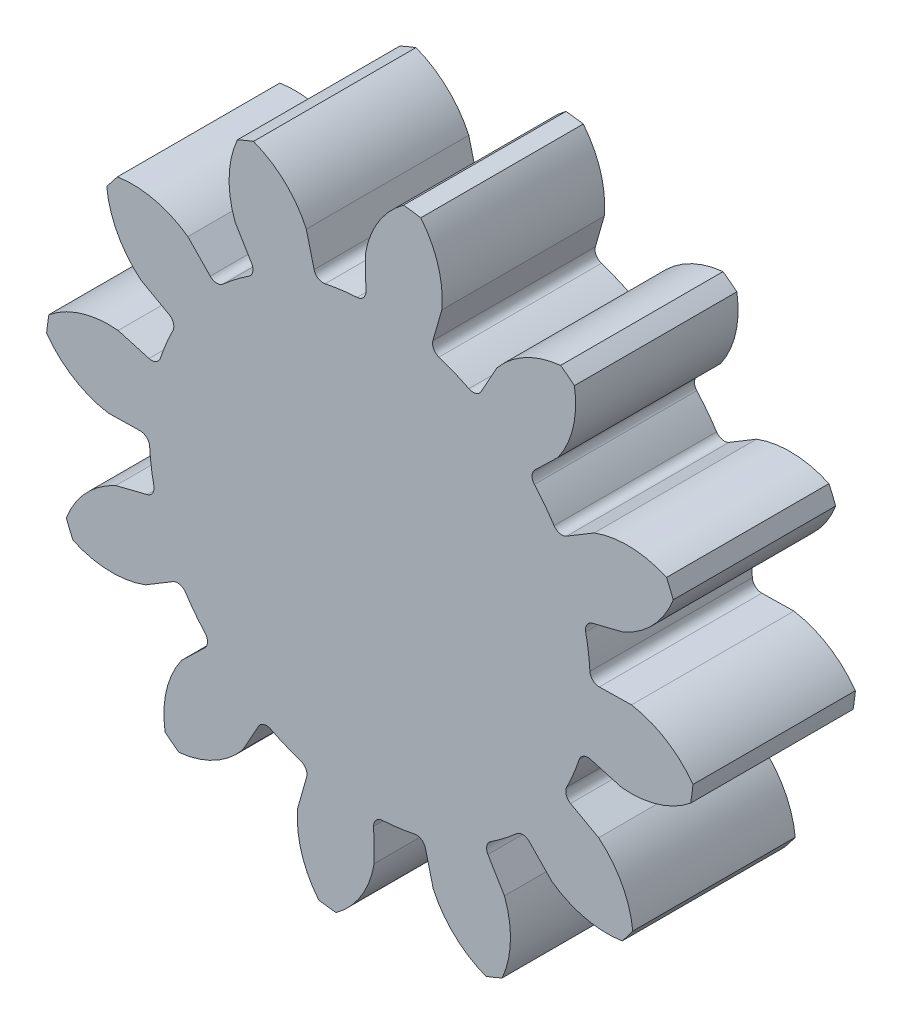
SolidWorks part; units mm, degrees
material "AISI 1045 钢，冷拔"
ref_plane "Front" through (0, 0, 0) normal (0, 0, 1) x (1, 0, 0)
ref_plane "Top" through (0, 0, 0) normal (0, 1, 0) x (1, 0, 0)
ref_plane "Right" through (0, 0, 0) normal (1, 0, 0) x (0, 0, -1)
sketch "草图1" plane through (0, 0, 0) normal (0, 0, 1) x (1, 0, 0)
  line L0 (0, 0) -> (-22.86, 0) construction
  line L1 (-22.86, 0) -> (-22.86, 5) construction
  line L2 (-22.86, 0) -> (-21.3149, 4.7553) construction
  line L3 (-22.86, 0) -> (-19.9211, 4.0451) construction
  line L4 (-22.86, 0) -> (-18.8149, 2.9389) construction
  line L5 (-22.86, 0) -> (-18.1047, 1.5451) construction
  line L6 (-22.86, 0) -> (-17.86, 0) construction
  line L7 (-22.86, 0) -> (-18.1047, -1.5451) construction
  line L8 (-22.86, 0) -> (-18.8149, -2.9389) construction
  line L9 (-22.86, 0) -> (-19.9211, -4.0451) construction
  line L10 (-22.86, 0) -> (-21.3149, -4.7553) construction
  line L11 (-22.86, 0) -> (-22.86, -5) construction
  line L12 (-22.86, 0) -> (-24.4051, -4.7553) construction
  line L21 (0, 0) -> (0, 8.5725) construction
  line L22 (-0.1365, 8.0544) -> (-0.1197, 7.0655)
  line L23 (0, 0) -> (1.3006, 9.8793) construction
  line L24 (0, 0) -> (-1.3054, 9.9157) construction
  line L25 (2.2165, 7.7446) -> (1.9443, 6.7938)
  line L26 (3.909, 7.0435) -> (3.4291, 6.1788)
  line L27 (5.7918, 5.5988) -> (5.0807, 4.9114)
  line L28 (6.907, 4.1454) -> (6.0591, 3.6365)
  line L29 (7.8152, 1.9528) -> (6.8558, 1.713)
  line L30 (8.0544, 0.1365) -> (7.0655, 0.1197)
  line L31 (7.7446, -2.2165) -> (6.7938, -1.9443)
  line L32 (7.0435, -3.909) -> (6.1788, -3.4291)
  line L33 (5.5988, -5.7918) -> (4.9114, -5.0807)
  line L34 (4.1454, -6.907) -> (3.6365, -6.0591)
  line L35 (1.9528, -7.8152) -> (1.713, -6.8558)
  line L36 (0.1365, -8.0544) -> (0.1197, -7.0655)
  line L37 (-2.2165, -7.7446) -> (-1.9443, -6.7938)
  line L38 (-3.909, -7.0435) -> (-3.4291, -6.1788)
  line L39 (-5.7918, -5.5988) -> (-5.0807, -4.9114)
  line L40 (-6.907, -4.1454) -> (-6.0591, -3.6365)
  line L41 (-7.8152, -1.9528) -> (-6.8558, -1.713)
  line L42 (-8.0544, -0.1365) -> (-7.0655, -0.1197)
  line L43 (-7.7446, 2.2165) -> (-6.7938, 1.9443)
  line L44 (-7.0435, 3.909) -> (-6.1788, 3.4291)
  line L45 (-5.5988, 5.7918) -> (-4.9114, 5.0807)
  line L46 (-4.1454, 6.907) -> (-3.6365, 6.0591)
  line L47 (-1.9528, 7.8152) -> (-1.713, 6.8558)
  line L56 (-22.86, 0) -> (-25.7989, -4.0451) construction
  line L57 (-22.86, 0) -> (-26.9051, -2.9389) construction
  line L58 (-22.86, 0) -> (-27.6153, -1.5451) construction
  line L59 (-22.86, 0) -> (-27.86, 0) construction
  line L60 (-22.86, 0) -> (-27.6153, 1.5451) construction
  line L61 (-22.86, 0) -> (-26.9051, 2.9389) construction
  line L62 (-22.86, 0) -> (-25.7989, 4.0451) construction
  line L63 (-22.86, 0) -> (-24.4051, 4.7553) construction
  circle A0 centre (0, 0) radius 6.7866 construction
  circle A1 centre (0, 0) radius 8.0555 construction
  circle A2 centre (0, 0) radius 8.5725 construction
  circle A3 centre (0, 0) radius 10.0012 construction
  arc A4 (0, 8.5725) -> (2.7551, 7.5697) centre (0, 4.2862) cw construction
  arc A5 (0, 8.5725) -> (-0.1365, 8.0544) centre (2.7551, 7.5697) ccw
  arc A6 (0, 8.5725) -> (1.0392, 9.9471) centre (2.7551, 7.5697) cw
  arc A7 (-0.3891, 6.7754) -> (-0.8858, 6.7285) centre (0, 0) ccw
  arc A8 (-0.3891, 6.7754) -> (-0.1197, 7.0655) centre (-0.4054, 7.0607) ccw
  arc A9 (1.0392, 9.9471) -> (1.5707, 9.8771) centre (0, 0) cw
  arc A10 (2.2187, 8.2804) -> (1.5707, 9.8771) centre (-0.7021, 8.0249) ccw
  arc A11 (2.2187, 8.2804) -> (2.2165, 7.7446) centre (-0.7021, 8.0249) cw
  arc A12 (2.1294, 6.4438) -> (1.9443, 6.7938) centre (2.2191, 6.7152) cw
  arc A13 (2.1294, 6.4438) -> (2.5971, 6.27) centre (0, 0) cw
  arc A14 (3.0508, 6.0622) -> (2.5971, 6.27) centre (0, 0) ccw
  arc A15 (3.0508, 6.0622) -> (3.4291, 6.1788) centre (3.1792, 6.3174) ccw
  arc A16 (4.2862, 7.424) -> (3.909, 7.0435) centre (6.1709, 5.178) ccw
  arc A17 (4.2862, 7.424) -> (5.8736, 8.0948) centre (6.1709, 5.178) cw
  arc A18 (5.8736, 8.0948) -> (6.2988, 7.7685) centre (0, 0) cw
  arc A19 (6.0617, 6.0617) -> (6.2988, 7.7685) centre (3.4044, 7.3008) ccw
  arc A20 (6.0617, 6.0617) -> (5.7918, 5.5988) centre (3.4044, 7.3008) cw
  arc A21 (5.066, 4.5158) -> (5.0807, 4.9114) centre (5.2793, 4.706) cw
  arc A22 (5.066, 4.5158) -> (5.3841, 4.1314) centre (0, 0) cw
  arc A23 (5.6731, 3.7246) -> (5.3841, 4.1314) centre (0, 0) ccw
  arc A24 (5.6731, 3.7246) -> (6.0591, 3.6365) centre (5.912, 3.8815) ccw
  arc A25 (7.424, 4.2863) -> (6.907, 4.1454) centre (7.9331, 1.3988) ccw
  arc A26 (7.424, 4.2863) -> (9.1341, 4.0736) centre (7.9331, 1.3988) cw
  arc A27 (9.1341, 4.0736) -> (9.3392, 3.5783) centre (0, 0) cw
  arc A28 (8.2804, 2.2187) -> (9.3392, 3.5783) centre (6.5987, 4.6205) ccw
  arc A29 (8.2804, 2.2187) -> (7.8152, 1.9528) centre (6.5987, 4.6205) cw
  arc A30 (6.6452, 1.3778) -> (6.8558, 1.713) centre (6.925, 1.4358) cw
  arc A31 (6.6452, 1.3778) -> (6.7285, 0.8858) centre (0, 0) cw
  arc A32 (6.7754, 0.3891) -> (6.7285, 0.8858) centre (0, 0) ccw
  arc A33 (6.7754, 0.3891) -> (7.0655, 0.1197) centre (7.0607, 0.4054) ccw
  arc A34 (8.5725, 0) -> (8.0544, 0.1365) centre (7.5697, -2.7551) ccw
  arc A35 (8.5725, 0) -> (9.9471, -1.0392) centre (7.5697, -2.7551) cw
  arc A36 (9.9471, -1.0392) -> (9.8771, -1.5707) centre (0, 0) cw
  arc A37 (8.2804, -2.2187) -> (9.8771, -1.5707) centre (8.0249, 0.7021) ccw
  arc A38 (8.2804, -2.2187) -> (7.7446, -2.2165) centre (8.0249, 0.7021) cw
  arc A39 (6.4438, -2.1294) -> (6.7938, -1.9443) centre (6.7152, -2.2191) cw
  arc A40 (6.4438, -2.1294) -> (6.27, -2.5971) centre (0, 0) cw
  arc A41 (6.0622, -3.0508) -> (6.27, -2.5971) centre (0, 0) ccw
  arc A42 (6.0622, -3.0508) -> (6.1788, -3.4291) centre (6.3174, -3.1792) ccw
  arc A43 (7.424, -4.2862) -> (7.0435, -3.909) centre (5.178, -6.1709) ccw
  arc A44 (7.424, -4.2862) -> (8.0948, -5.8736) centre (5.178, -6.1709) cw
  arc A45 (8.0948, -5.8736) -> (7.7685, -6.2988) centre (0, 0) cw
  arc A46 (6.0617, -6.0617) -> (7.7685, -6.2988) centre (7.3008, -3.4044) ccw
  arc A47 (6.0617, -6.0617) -> (5.5988, -5.7918) centre (7.3008, -3.4044) cw
  arc A48 (4.5158, -5.066) -> (4.9114, -5.0807) centre (4.706, -5.2793) cw
  arc A49 (4.5158, -5.066) -> (4.1314, -5.3841) centre (0, 0) cw
  arc A50 (3.7246, -5.6731) -> (4.1314, -5.3841) centre (0, 0) ccw
  arc A51 (3.7246, -5.6731) -> (3.6365, -6.0591) centre (3.8815, -5.912) ccw
  arc A52 (4.2863, -7.424) -> (4.1454, -6.907) centre (1.3988, -7.9331) ccw
  arc A53 (4.2863, -7.424) -> (4.0736, -9.1341) centre (1.3988, -7.9331) cw
  arc A54 (4.0736, -9.1341) -> (3.5783, -9.3392) centre (0, 0) cw
  arc A55 (2.2187, -8.2804) -> (3.5783, -9.3392) centre (4.6205, -6.5987) ccw
  arc A56 (2.2187, -8.2804) -> (1.9528, -7.8152) centre (4.6205, -6.5987) cw
  arc A57 (1.3778, -6.6452) -> (1.713, -6.8558) centre (1.4358, -6.925) cw
  arc A58 (1.3778, -6.6452) -> (0.8858, -6.7285) centre (0, 0) cw
  arc A59 (0.3891, -6.7754) -> (0.8858, -6.7285) centre (0, 0) ccw
  arc A60 (0.3891, -6.7754) -> (0.1197, -7.0655) centre (0.4054, -7.0607) ccw
  arc A61 (0, -8.5725) -> (0.1365, -8.0544) centre (-2.7551, -7.5697) ccw
  arc A62 (0, -8.5725) -> (-1.0392, -9.9471) centre (-2.7551, -7.5697) cw
  arc A63 (-1.0392, -9.9471) -> (-1.5707, -9.8771) centre (0, 0) cw
  arc A64 (-2.2187, -8.2804) -> (-1.5707, -9.8771) centre (0.7021, -8.0249) ccw
  arc A65 (-2.2187, -8.2804) -> (-2.2165, -7.7446) centre (0.7021, -8.0249) cw
  arc A66 (-2.1294, -6.4438) -> (-1.9443, -6.7938) centre (-2.2191, -6.7152) cw
  arc A67 (-2.1294, -6.4438) -> (-2.5971, -6.27) centre (0, 0) cw
  arc A68 (-3.0508, -6.0622) -> (-2.5971, -6.27) centre (0, 0) ccw
  arc A69 (-3.0508, -6.0622) -> (-3.4291, -6.1788) centre (-3.1792, -6.3174) ccw
  arc A70 (-4.2862, -7.424) -> (-3.909, -7.0435) centre (-6.1709, -5.178) ccw
  arc A71 (-4.2862, -7.424) -> (-5.8736, -8.0948) centre (-6.1709, -5.178) cw
  arc A72 (-5.8736, -8.0948) -> (-6.2988, -7.7685) centre (0, 0) cw
  arc A73 (-6.0617, -6.0617) -> (-6.2988, -7.7685) centre (-3.4044, -7.3008) ccw
  arc A74 (-6.0617, -6.0617) -> (-5.7918, -5.5988) centre (-3.4044, -7.3008) cw
  arc A75 (-5.066, -4.5158) -> (-5.0807, -4.9114) centre (-5.2793, -4.706) cw
  arc A76 (-5.066, -4.5158) -> (-5.3841, -4.1314) centre (0, 0) cw
  arc A77 (-5.6731, -3.7246) -> (-5.3841, -4.1314) centre (0, 0) ccw
  arc A78 (-5.6731, -3.7246) -> (-6.0591, -3.6365) centre (-5.912, -3.8815) ccw
  arc A79 (-7.424, -4.2863) -> (-6.907, -4.1454) centre (-7.9331, -1.3988) ccw
  arc A80 (-7.424, -4.2863) -> (-9.1341, -4.0736) centre (-7.9331, -1.3988) cw
  arc A81 (-9.1341, -4.0736) -> (-9.3392, -3.5783) centre (0, 0) cw
  arc A82 (-8.2804, -2.2187) -> (-9.3392, -3.5783) centre (-6.5987, -4.6205) ccw
  arc A83 (-8.2804, -2.2187) -> (-7.8152, -1.9528) centre (-6.5987, -4.6205) cw
  arc A84 (-6.6452, -1.3778) -> (-6.8558, -1.713) centre (-6.925, -1.4358) cw
  arc A85 (-6.6452, -1.3778) -> (-6.7285, -0.8858) centre (0, 0) cw
  arc A86 (-6.7754, -0.3891) -> (-6.7285, -0.8858) centre (0, 0) ccw
  arc A87 (-6.7754, -0.3891) -> (-7.0655, -0.1197) centre (-7.0607, -0.4054) ccw
  arc A88 (-8.5725, 0) -> (-8.0544, -0.1365) centre (-7.5697, 2.7551) ccw
  arc A89 (-8.5725, 0) -> (-9.9471, 1.0392) centre (-7.5697, 2.7551) cw
  arc A90 (-9.9471, 1.0392) -> (-9.8771, 1.5707) centre (0, 0) cw
  arc A91 (-8.2804, 2.2187) -> (-9.8771, 1.5707) centre (-8.0249, -0.7021) ccw
  arc A92 (-8.2804, 2.2187) -> (-7.7446, 2.2165) centre (-8.0249, -0.7021) cw
  arc A93 (-6.4438, 2.1294) -> (-6.7938, 1.9443) centre (-6.7152, 2.2191) cw
  arc A94 (-6.4438, 2.1294) -> (-6.27, 2.5971) centre (0, 0) cw
  arc A95 (-6.0622, 3.0508) -> (-6.27, 2.5971) centre (0, 0) ccw
  arc A96 (-6.0622, 3.0508) -> (-6.1788, 3.4291) centre (-6.3174, 3.1792) ccw
  arc A97 (-7.424, 4.2862) -> (-7.0435, 3.909) centre (-5.178, 6.1709) ccw
  arc A98 (-7.424, 4.2862) -> (-8.0948, 5.8736) centre (-5.178, 6.1709) cw
  arc A99 (-8.0948, 5.8736) -> (-7.7685, 6.2988) centre (0, 0) cw
  arc A100 (-6.0617, 6.0617) -> (-7.7685, 6.2988) centre (-7.3008, 3.4044) ccw
  arc A101 (-6.0617, 6.0617) -> (-5.5988, 5.7918) centre (-7.3008, 3.4044) cw
  arc A102 (-4.5158, 5.066) -> (-4.9114, 5.0807) centre (-4.706, 5.2793) cw
  arc A103 (-4.5158, 5.066) -> (-4.1314, 5.3841) centre (0, 0) cw
  arc A104 (-3.7246, 5.6731) -> (-4.1314, 5.3841) centre (0, 0) ccw
  arc A105 (-3.7246, 5.6731) -> (-3.6365, 6.0591) centre (-3.8815, 5.912) ccw
  arc A106 (-4.2863, 7.424) -> (-4.1454, 6.907) centre (-1.3988, 7.9331) ccw
  arc A107 (-4.2863, 7.424) -> (-4.0736, 9.1341) centre (-1.3988, 7.9331) cw
  arc A108 (-4.0736, 9.1341) -> (-3.5783, 9.3392) centre (0, 0) cw
  arc A109 (-2.2187, 8.2804) -> (-3.5783, 9.3392) centre (-4.6205, 6.5987) ccw
  arc A110 (-2.2187, 8.2804) -> (-1.9528, 7.8152) centre (-4.6205, 6.5987) cw
  arc A111 (-1.3778, 6.6452) -> (-1.713, 6.8558) centre (-1.4358, 6.925) cw
  arc A112 (-1.3778, 6.6452) -> (-0.8858, 6.7285) centre (0, 0) cw
  point P26 (-22.86, 0)
  point P28 (0, 4.2862)
  point P30 (0, 8.5725)
  point P44 (-0.115, 6.7856)
  point P230 (0, 0)
  dimension "齿根圆直径" = 13.5731
  dimension "基圆直径" = 16.111
  dimension "分度圆直径" = 17.145
  dimension "齿顶圆直径" = 20.0025
  dimension "齿根圆角半径" = 0.2858
  dimension "中心距" = 22.86
  dimension "D2" = 5
  dimension "对称角度1" = 7.5
  dimension "对称角度2" = 7.5
  dimension "第二齿轮齿数" = 20
  dimension "齿轮齿数" = 12
extrude "凸台-拉伸1" add sketch "草图1" along normal mid plane 5 contours A112 A111 L47 A110 A109 A108 A107 A106 L46 A105 A104 A103 A102 L45 A101 A100 A99 A98 A97 L44 A96 A95 A94 A93 L43 A92 A91 A90 A89 A88 L42 A87 A86 A85 A84 L41 A83 A82 A81 A80 A79 L40 A78 A77 A76 A75 L39 A74 A73 A72 A71
other "PropertyManager"
